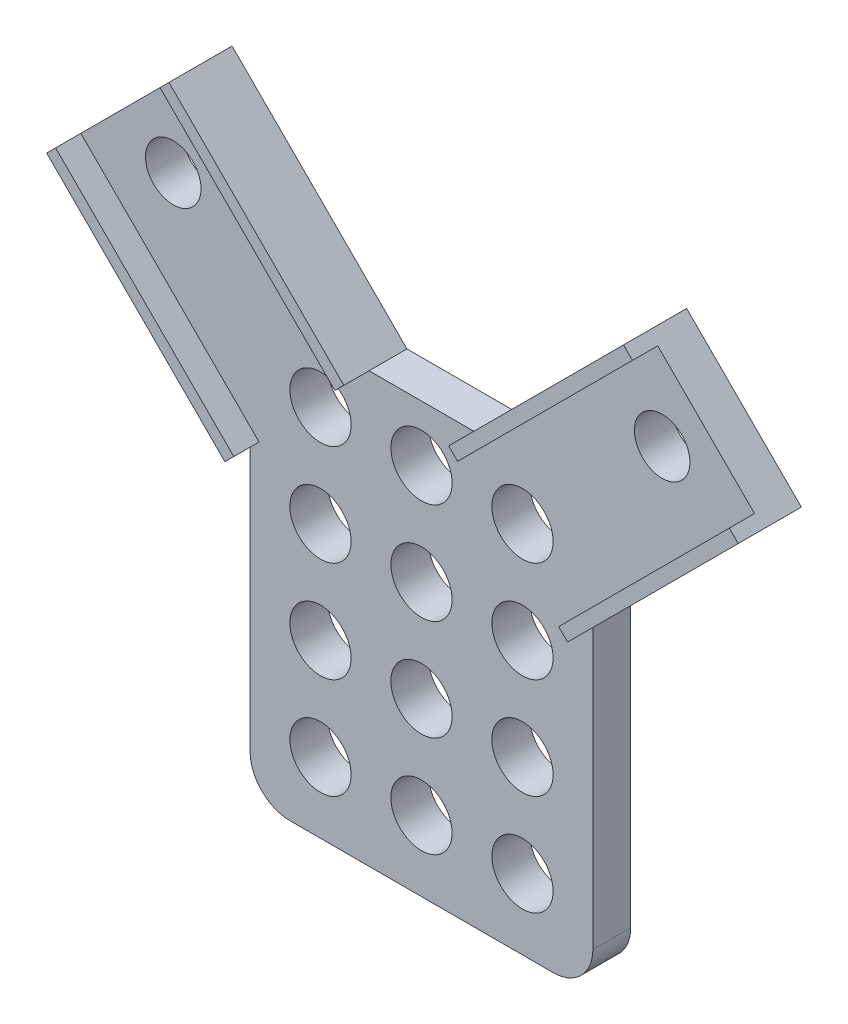
SolidWorks part; units mm, degrees
ref_plane "Front Plane" through (0, 0, 0) normal (0, 0, 1) x (1, 0, 0)
ref_plane "Top Plane" through (0, 0, 0) normal (0, 1, 0) x (1, 0, 0)
ref_plane "Right Plane" through (0, 0, 0) normal (1, 0, 0) x (0, 0, -1)
sketch "Sketch1" plane through (0, 0, 0) normal (0, 0, 1) x (1, 0, 0)
  line L1 (3.15, 0) -> (24, 0)
  line L2 (0, 3.15) -> (0, 34)
  line L3 (0, 34) -> (27.15, 34)
  line L4 (27.15, 3.15) -> (27.15, 34)
  arc A0 (3.15, 0) -> (0, 3.15) centre (3.15, 3.15) cw
  arc A1 (24, 0) -> (27.15, 3.15) centre (24, 3.15) ccw
  point P7 (0, 0)
  point P10 (27.15, 0)
  dimension "D3" = 3.15
  dimension "D4" = 3.15
  dimension "D1" = 27.15
  dimension "D2" = 34
extrude "Boss-Extrude1" add sketch "Sketch1" along normal blind 3
sketch "Sketch2" plane through (0, 0, 3) normal (0, 0, 1) x (1, 0, 0)
  line L1 (0, 34) -> (0, 3.15) construction
  line L3 (3.15, 0) -> (24, 0) construction
  circle A0 centre (5.575, 5.575) radius 2.425
  circle A1 centre (13.575, 5.575) radius 2.425
  circle A2 centre (21.575, 5.575) radius 2.425
  circle A3 centre (13.575, 13.575) radius 2.425
  circle A4 centre (21.575, 13.575) radius 2.425
  circle A5 centre (5.575, 13.575) radius 2.425
  circle A6 centre (13.575, 21.575) radius 2.425
  circle A7 centre (21.575, 21.575) radius 2.425
  circle A8 centre (5.575, 21.575) radius 2.425
  circle A9 centre (5.575, 29.575) radius 2.425
  circle A10 centre (13.575, 29.575) radius 2.425
  circle A11 centre (21.575, 29.575) radius 2.425
  dimension "D1" = 4.85
  dimension "D2" = 4.85
  dimension "D3" = 4.85
  dimension "D4" = 3.15
  dimension "D5" = 3.15
  dimension "D6" = 3.15
  dimension "D7" = 3.15
  dimension "D8" = 3.15
  dimension "D9" = 3.15
  dimension "D10" = 4.85
  dimension "D11" = 4.85
  dimension "D12" = 4.85
  dimension "D13" = 3.15
  dimension "D14" = 3.15
  dimension "D15" = 3.15
  dimension "D16" = 3.15
  dimension "D17" = 3.15
  dimension "D18" = 3.15
  dimension "D19" = 4.85
  dimension "D20" = 4.85
  dimension "D21" = 4.85
  dimension "D22" = 3.15
  dimension "D23" = 3.15
  dimension "D24" = 3.15
  dimension "D25" = 3.15
  dimension "D26" = 3.15
  dimension "D27" = 3.15
  dimension "D28" = 4.85
  dimension "D29" = 4.85
  dimension "D30" = 4.85
  dimension "D31" = 3.15
  dimension "D32" = 3.15
  dimension "D33" = 3.15
  dimension "D34" = 3.15
  dimension "D35" = 3.15
  dimension "D36" = 3.15
extrude "Cut-Extrude1" cut sketch "Sketch2" against normal blind 3
sketch "Sketch3" plane through (0, 0, 0) normal (0, 0, 1) x (1, 0, 0)
  line L0 (0.0242, 24.0242) -> (9.7116, 33.7116)
  line L1 (0.0242, 24.0242) -> (-14.1179, 38.1663)
  line L2 (9.7116, 33.7116) -> (-4.4306, 47.8537)
  line L3 (-14.1179, 38.1663) -> (-4.4306, 47.8537)
  line L5 (0, 34) -> (0, 3.15) construction
  line L6 (17.4384, 33.7116) -> (26.5247, 24.6253)
  line L7 (17.4384, 33.7116) -> (31.5806, 47.8537)
  line L8 (26.5247, 24.6253) -> (40.6669, 38.7674)
  line L9 (31.5806, 47.8537) -> (40.6669, 38.7674)
  line L10 (27.15, 3.15) -> (27.15, 34) construction
  circle A0 centre (5.575, 29.575) radius 2.425 construction
  circle A1 centre (21.575, 29.575) radius 2.425 construction
  dimension "D1" = 0
  dimension "D2" = 7.85
  dimension "D8" = 5.85
  dimension "D3" = 5.85
  dimension "D4" = 20
  dimension "D5" = 45
  dimension "D6" = 0
  dimension "D7" = 20
  dimension "D9" = 7
  dimension "D10" = 45
extrude "Boss-Extrude3" add sketch "Sketch3" along normal blind 3
sketch "Sketch6" plane through (0, 0, 3) normal (0, 0, 1) x (1, 0, 0)
  line L0 (-14.1179, 38.1663) -> (0, 24.0484)
  line L1 (-14.1179, 38.1663) -> (-13.4102, 38.874)
  line L2 (0, 24.0484) -> (0.7077, 24.7561)
  line L3 (-13.4102, 38.874) -> (0.7077, 24.7561)
  line L4 (-4.4306, 47.8537) -> (9.4231, 34)
  line L5 (-4.4306, 47.8537) -> (-5.1377, 47.1466)
  line L6 (9.4231, 34) -> (8.716, 33.2929)
  line L7 (-5.1377, 47.1466) -> (8.716, 33.2929)
  line L8 (17.7269, 34) -> (31.5806, 47.8537)
  line L9 (17.7269, 34) -> (18.434, 33.2929)
  line L10 (31.5806, 47.8537) -> (32.2877, 47.1466)
  line L11 (18.434, 33.2929) -> (32.2877, 47.1466)
  line L12 (27.15, 25.2505) -> (40.6669, 38.7674)
  line L13 (27.15, 25.2505) -> (26.4429, 25.9576)
  line L14 (40.6669, 38.7674) -> (39.9598, 39.4745)
  line L15 (26.4429, 25.9576) -> (39.9598, 39.4745)
  dimension "D1" = 1.0008
  dimension "D2" = 1
  dimension "D3" = 1
  dimension "D4" = 1
extrude "Boss-Extrude4" add sketch "Sketch6" along normal blind 2
sketch "Sketch7" plane through (0, 0, 3) normal (0, 0, 1) x (1, 0, 0)
  line L0 (3.8603, 27.8603) -> (7.2897, 31.2897) construction
  line L1 (19.8603, 31.2897) -> (23.2897, 27.8603) construction
  line L4 (0.7077, 24.7561) -> (-13.4102, 38.874) construction
  line L5 (-5.1377, 47.1466) -> (-13.4102, 38.874) construction
  line L6 (39.9598, 39.4745) -> (32.2877, 47.1466) construction
  line L7 (39.9598, 39.4745) -> (26.4429, 25.9576) construction
  circle A0 centre (5.575, 29.575) radius 2.425
  circle A1 centre (21.575, 29.575) radius 2.425
  circle A2 centre (-6.0917, 39.8286) radius 2.2
  circle A3 centre (32.6412, 40.4291) radius 2.2
  dimension "D1" = 4.85
  dimension "D2" = 4.85
  dimension "D3" = 4.4
  dimension "D4" = 5.85
  dimension "D5" = 4.5
  dimension "D6" = 4.4
  dimension "D7" = 4.5
  dimension "D8" = 5.85
extrude "Cut-Extrude4" cut sketch "Sketch7" against normal blind 12
